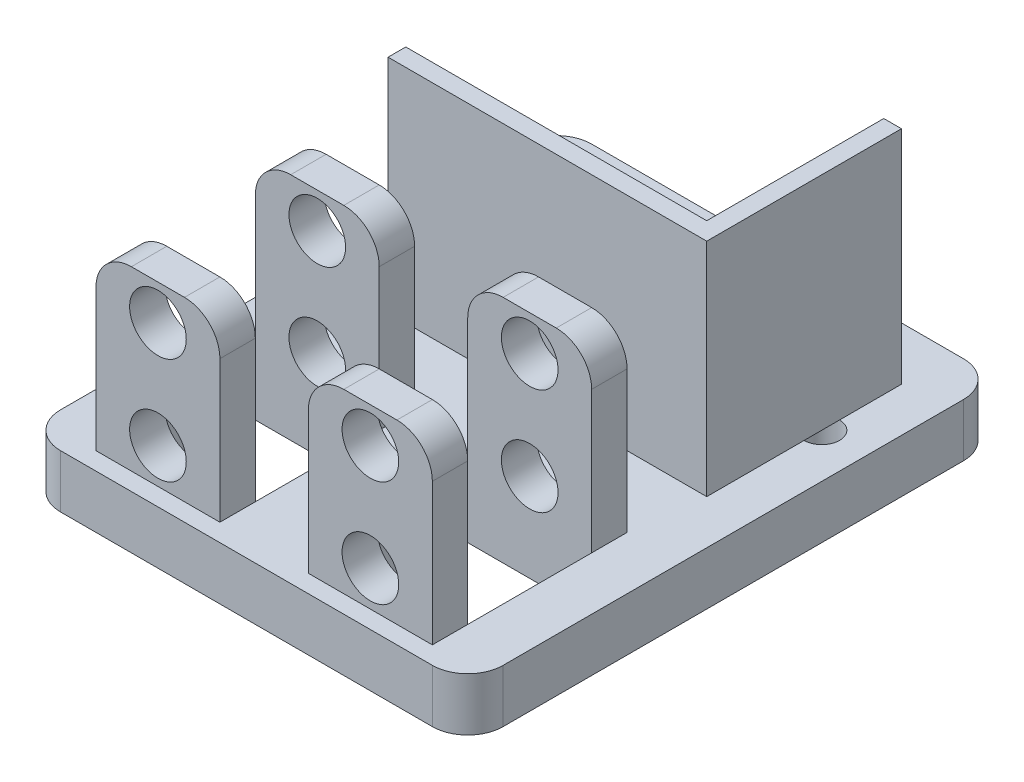
SolidWorks part; units mm, degrees
ref_plane "前视基准面" through (0, 0, 0) normal (0, 0, 1) x (1, 0, 0)
ref_plane "上视基准面" through (0, 0, 0) normal (0, 1, 0) x (1, 0, 0)
ref_plane "右视基准面" through (0, 0, 0) normal (1, 0, 0) x (0, 0, -1)
other "Configuration Table"
sketch "草图1" plane through (0, 0, 0) normal (0, 1, 0) x (1, 0, 0)
  line L0 (0, -13.2677) -> (0, 12.7032) construction
  line L1 (-10.5, -15) -> (10.5, -15)
  line L2 (-12.5, -13) -> (-12.5, 13)
  line L3 (-10.5, 15) -> (10.5, 15)
  line L4 (12.5, -13) -> (12.5, 13)
  line L5 (-12.5, -15) -> (12.5, 15) construction
  line L6 (-12.5, 15) -> (12.5, -15) construction
  line L7 (18.5568, 7.5) -> (-26.2259, 7.5) construction
  line L8 (-8, 3) -> (8, 3)
  line L9 (-8, 3) -> (-8, 12)
  line L10 (-8, 12) -> (8, 12)
  line L11 (8, 3) -> (8, 12)
  line L12 (-8, 3) -> (8, 12) construction
  line L13 (-8, 12) -> (8, 3) construction
  line L14 (2.5, -12) -> (9.5, -12)
  line L15 (-2.5, -12) -> (-9.5, -12)
  line L16 (-2.5, -12) -> (-2.5, -5)
  line L17 (-2.5, -5) -> (-9.5, -5)
  line L18 (-9.5, -12) -> (-9.5, -5)
  line L19 (2.5, -12) -> (2.5, -5)
  line L20 (2.5, -5) -> (9.5, -5)
  line L21 (9.5, -12) -> (9.5, -5)
  circle A1 centre (-10, 7.5) radius 1
  circle A2 centre (10, 7.5) radius 1
  arc A4 (-10.5, -15) -> (-12.5, -13) centre (-10.5, -13) cw
  arc A5 (10.5, -15) -> (12.5, -13) centre (10.5, -13) ccw
  arc A6 (10.5, 15) -> (12.5, 13) centre (10.5, 13) cw
  arc A7 (-12.5, 13) -> (-10.5, 15) centre (-10.5, 13) cw
  point P0 (0, 0)
  point P10 (0, 7.5)
  dimension "D2" = 7
  dimension "D7" = 2
  dimension "D8" = 10
  dimension "D10" = 2
  dimension "D3" = 9
  dimension "D4" = 16
  dimension "D5" = 3
  dimension "D6" = 30
  dimension "D9" = 25
  dimension "D11" = 7
  dimension "D12" = 3
  dimension "D13" = 3
extrude "凸台-拉伸1" add sketch "草图1" along normal blind 3
sketch "草图2" plane through (0, 3, 0) normal (0, 1, 0) x (1, 0, 0)
  line L0 (9.5, -12) -> (9.5, -5) construction
  line L1 (-9.5, -5) -> (-2.5, -5)
  line L2 (-9.5, -5) -> (-9.5, -3)
  line L3 (-9.5, -3) -> (-2.5, -3)
  line L4 (-2.5, -5) -> (-2.5, -3)
  line L5 (-9.5, -12) -> (-2.5, -12)
  line L6 (-9.5, -12) -> (-9.5, -14)
  line L7 (-9.5, -14) -> (-2.5, -14)
  line L8 (-2.5, -12) -> (-2.5, -14)
  line L9 (2.5, -5) -> (9.5, -5)
  line L10 (2.5, -5) -> (2.5, -3)
  line L11 (2.5, -3) -> (9.5, -3)
  line L12 (9.5, -5) -> (9.5, -3)
  line L13 (2.5, -12) -> (9.5, -12)
  line L14 (2.5, -12) -> (2.5, -14)
  line L15 (2.5, -14) -> (9.5, -14)
  line L16 (9.5, -12) -> (9.5, -14)
  line L17 (-2.5, -12) -> (-2.5, -5) construction
  dimension "D1" = 2
  dimension "D2" = 2
  dimension "D3" = 2
  dimension "D4" = 2
extrude "凸台-拉伸2" add sketch "草图2" along normal blind 10
sketch "草图3" plane through (0, 0, 14) normal (0, 0, 1) x (1, 0, 0)
  line L0 (6, 3) -> (6, 13) construction
  line L1 (2.5, 3) -> (9.5, 3) construction
  line L2 (2.5, 13) -> (9.5, 13) construction
  line L3 (-6, 3) -> (-6, 13) construction
  line L4 (-9.5, 3) -> (-2.5, 3) construction
  line L5 (-9.5, 13) -> (-2.5, 13) construction
  line L6 (-10.5, 3) -> (10.5, 3) construction
  circle A0 centre (-6, 11) radius 1.6
  circle A1 centre (-6, 5) radius 1.6
  circle A2 centre (6, 11) radius 1.6
  circle A3 centre (6, 5) radius 1.6
  dimension "D1" = 3.2
  dimension "D2" = 3.2
  dimension "D3" = 3.2
  dimension "D4" = 3.2
  dimension "D5" = 6
  dimension "D6" = 6
  dimension "D7" = 2
  dimension "D8" = 2
extrude "切除-拉伸1" cut sketch "草图3" against normal through all and the other way through all
fillet "圆角1" radius 2 8 edges at (-9.5, 13, 4) (-2.5, 13, 4) (2.5, 13, 4) (9.5, 13, 4) (-9.5, 13, 13) (-2.5, 13, 13) (2.5, 13, 13) (9.5, 13, 13)
sketch "草图4" plane through (0, 0, 0) normal (0, -1, 0) x (1, 0, 0)
  line L0 (-8, -7.5) -> (-18.6857, -7.5) construction
  line L1 (-8, -12) -> (-8, -3) construction
  line L2 (-8, -5.75) -> (-9.2, -5.75)
  line L3 (-9.2, -5.75) -> (-9.2, -9.25)
  line L4 (-8, -5.75) -> (-8, -9.25)
  line L5 (-8, -9.25) -> (-9.2, -9.25)
  point P9 (-9.2, -7.5)
  dimension "D1" = 3.5
  dimension "D2" = 1.2
extrude "切除-拉伸3" cut sketch "草图4" against normal blind 10
sketch "草图5" plane through (0, 3, 0) normal (0, 1, 0) x (1, 0, 0)
  line L0 (-8, 3) -> (-8, 1)
  line L1 (-8, 1) -> (10, 1)
  line L2 (10, 1) -> (10, 12)
  line L3 (10, 12) -> (8, 12)
  line L4 (8, 12) -> (8, 3)
  line L5 (8, 3) -> (-8, 3)
  dimension "D1" = 2
  dimension "D2" = 2
extrude "凸台-拉伸3" add sketch "草图5" along normal blind 7.5
sketch "草图6" plane through (0, 10.5, 0) normal (0, 1, 0) x (1, 0, 0)
  line L1 (10, 1) -> (-8, 1)
  line L2 (10, 1) -> (10, 12)
  line L3 (10, 12) -> (-8, 12)
  line L4 (-8, 1) -> (-8, 12)
extrude "凸台-拉伸4" [suppressed] add sketch "草图6" along normal blind 2
sketch "草图7" [suppressed] plane through (0, 12.5, 0) normal (0, 1, 0) x (1, 0, 0)
  line L0 (-8, 6.5) -> (18.069, 6.5) construction
  line L1 (-8, 12) -> (-8, 1) construction
  circle A0 centre (-3, 6.5) radius 2
  dimension "D1" = 4
  dimension "D2" = 5
extrude "凸台-拉伸5" [suppressed] add sketch "草图7" along normal blind 5
sketch "草图8" plane through (0, 10.5, 0) normal (0, 1, 0) x (1, 0, 0)
  line L0 (-8, 1) -> (-8, 2)
  line L1 (-8, 3) -> (-8, 1) construction
  line L2 (-8, 2) -> (9, 2)
  line L3 (9, 2) -> (9, 12)
  line L4 (10, 12) -> (8, 12) construction
  line L5 (9, 12) -> (10, 12)
  line L6 (10, 12) -> (10, 1)
  line L7 (10, 1) -> (-8, 1)
extrude "凸台-拉伸6" add sketch "草图8" along normal blind 5
